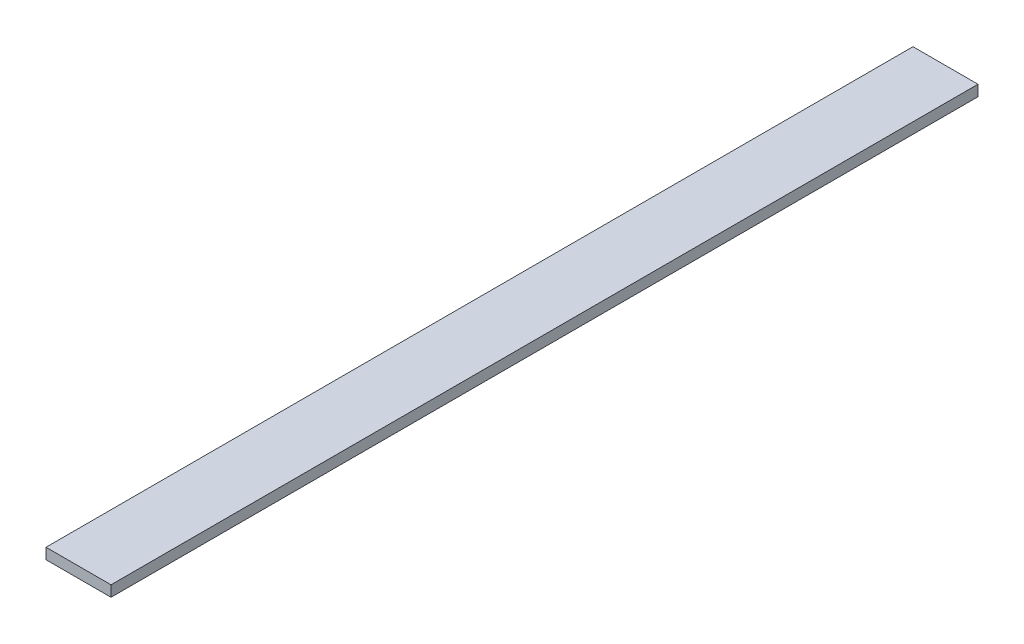
SolidWorks part; units mm, degrees
ref_plane "前视基准面" through (0, 0, 0) normal (0, 0, 1) x (1, 0, 0)
ref_plane "上视基准面" through (0, 0, 0) normal (0, 1, 0) x (1, 0, 0)
ref_plane "右视基准面" through (0, 0, 0) normal (1, 0, 0) x (0, 0, -1)
other "Configuration Table"
sketch "草图13" plane through (0, 0, 0) normal (0, 1, 0) x (1, 0, 0)
  line L1 (0, 0) -> (15, 0)
  line L2 (0, 0) -> (0, -200)
  line L3 (0, -200) -> (15, -200)
  line L4 (15, 0) -> (15, -200)
  dimension "D2" = 200
extrude "凸台-拉伸4" add sketch "草图13" along normal blind 2.5
